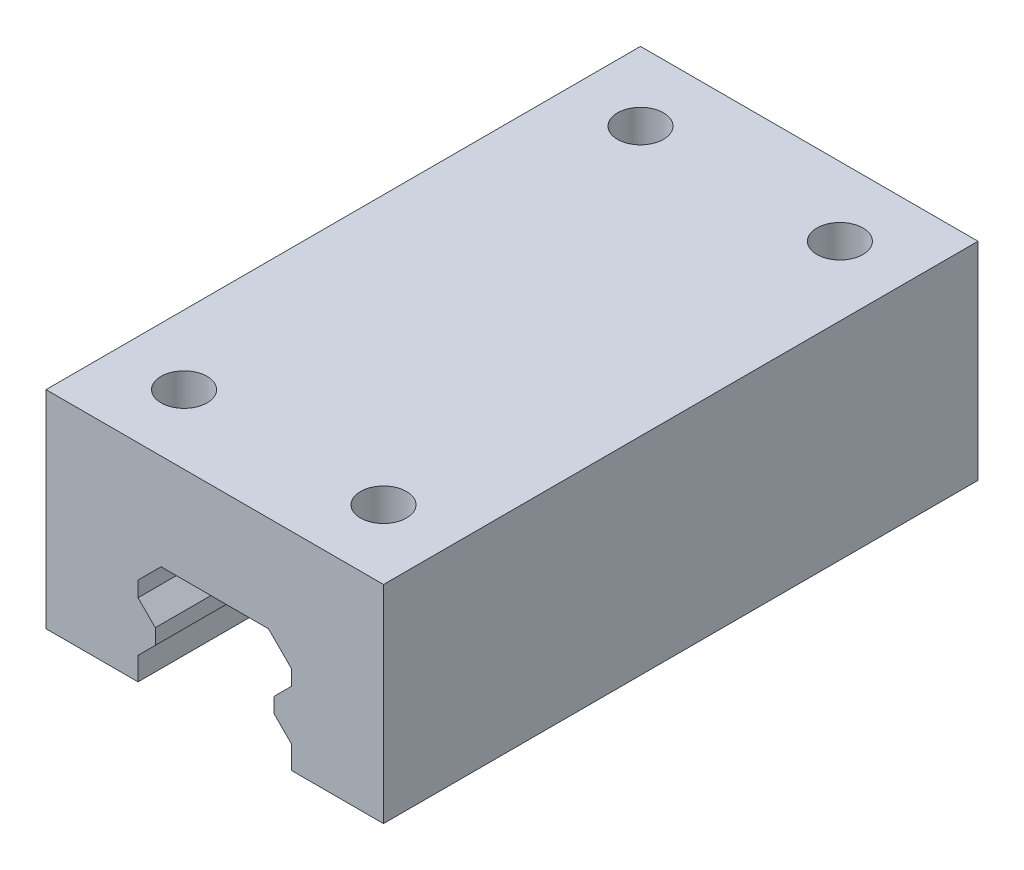
SolidWorks part; units mm, degrees
material "1023 Carbon Steel Sheet (SS)"
ref_plane "Front" through (0, 0, 0) normal (0, 0, 1) x (1, 0, 0)
ref_plane "Top" through (0, 0, 0) normal (0, 1, 0) x (1, 0, 0)
ref_plane "Right" through (0, 0, 0) normal (1, 0, 0) x (0, 0, -1)
sketch "Sketch1" plane through (0, 0, 0) normal (0, 0, 1) x (1, 0, 0)
  line L0 (0, 19.8343) -> (0, 32.3343)
  line L1 (22, 32.3343) -> (-22, 32.3343)
  line L2 (-22, 32.3343) -> (-22, 5.3343)
  line L4 (-10, 5.3343) -> (-10, 8.3343)
  line L5 (-10, 8.3343) -> (-7.75, 10.5843)
  line L6 (-7.75, 10.5843) -> (-7.75, 12.5843)
  line L7 (-7.75, 12.5843) -> (-10, 14.8343)
  line L8 (-10, 14.8343) -> (-10, 16.8343)
  line L9 (-10, 16.8343) -> (-7, 19.8343)
  line L10 (-7, 19.8343) -> (7, 19.8343)
  line L12 (-22, 5.3343) -> (-10, 5.3343)
  line L13 (0, 0) -> (0, 33.8462) construction
  line L14 (22, 5.3343) -> (10, 5.3343)
  line L15 (10, 16.8343) -> (7, 19.8343)
  line L16 (10, 14.8343) -> (10, 16.8343)
  line L17 (7.75, 12.5843) -> (10, 14.8343)
  line L18 (7.75, 10.5843) -> (7.75, 12.5843)
  line L19 (10, 8.3343) -> (7.75, 10.5843)
  line L20 (10, 5.3343) -> (10, 8.3343)
  line L21 (22, 32.3343) -> (22, 5.3343)
  dimension "D1" = 27
  dimension "D2" = 7
  dimension "D3" = 10
  dimension "D4" = 10
  dimension "D5" = 135
  dimension "D6" = 2
  dimension "D7" = 2
  dimension "D8" = 14.5
  dimension "D9" = 3
  dimension "D10" = 44
extrude "Boss-Extrude1" add sketch "Sketch1" against normal blind 77.5 contours L21 L1 L0 L10 L15 L16 L17 L18 L19 L20 L14 | L2 L12 L4 L5 L6 L7 L8 L9 L10 L0 L1
sketch "Sketch2" plane through (0, 32.3343, 0) normal (0, 1, 0) x (1, 0, 0)
  line L0 (0, 0) -> (0, 77.5) construction
  line L1 (22, 77.5) -> (-22, 77.5) construction
  line L2 (-22, 77.5) -> (-22, 0) construction
  line L3 (22, 0) -> (-22, 0) construction
  circle A0 centre (-13, 9) radius 3
  circle A1 centre (-13, 68.5) radius 3
  circle A2 centre (13, 68.5) radius 3
  circle A3 centre (13, 9) radius 3
  dimension "D3" = 6
  dimension "D4" = 6
  dimension "D6" = 9
  dimension "D1" = 9
  dimension "D2" = 9
  dimension "D5" = 9
extrude "Cut-Extrude1" cut sketch "Sketch2" against normal blind 10
